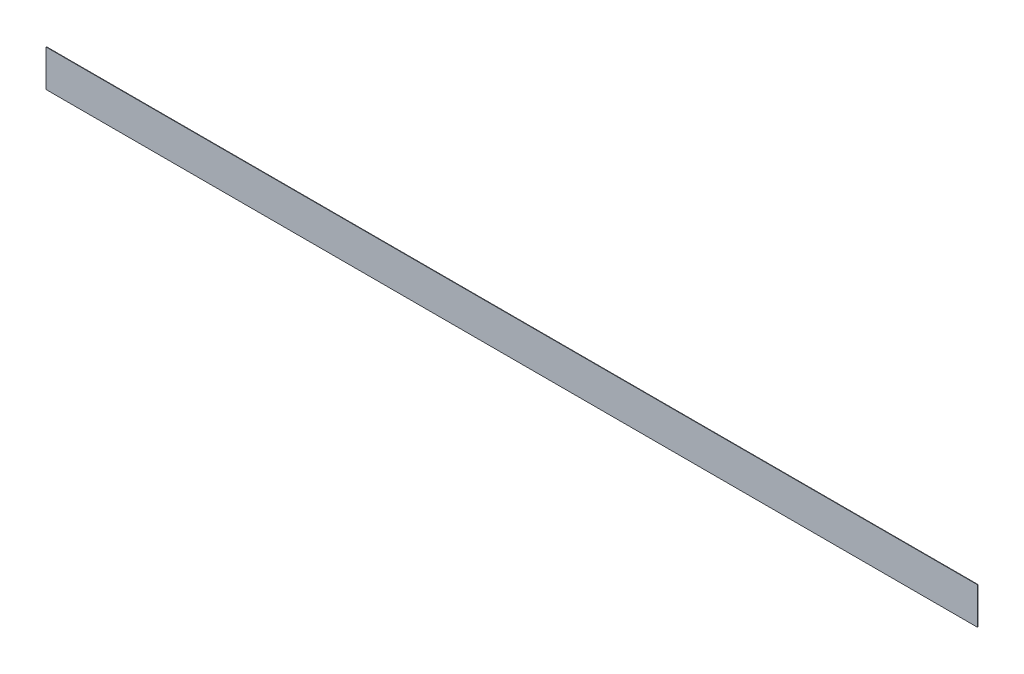
SolidWorks part; units mm, degrees
ref_plane "Front Plane" through (0, 0, 0) normal (0, 0, 1) x (1, 0, 0)
ref_plane "Top Plane" through (0, 0, 0) normal (0, 1, 0) x (1, 0, 0)
ref_plane "Right Plane" through (0, 0, 0) normal (1, 0, 0) x (0, 0, -1)
sketch "Sketch1" plane through (0, 0, 0) normal (0, 0, 1) x (1, 0, 0)
  line L0 (-12838.1061, 0) -> (-12838.1061, 482.6) construction
  line L1 (0, 0) -> (-12838.1061, 0)
  line L2 (0, 0) -> (0, 508)
  line L3 (0, 508) -> (-12838.1061, 508)
  line L4 (0, 0) -> (0, 482.6)
  line L5 (0, 482.6) -> (-336.55, 482.6)
  line L6 (-336.55, 482.6) -> (-336.55, 0)
  line L7 (-336.55, 0) -> (0, 0)
  line L8 (0, 0) -> (0, 482.6)
  line L9 (0, 482.6) -> (-336.55, 482.6)
  line L10 (-336.55, 482.6) -> (-336.55, 0)
  line L11 (-336.55, 0) -> (0, 0)
  line L12 (-12838.1061, 0) -> (-12838.1061, 508)
  line L14 (-12493.625, 508) -> (-11350.625, 508) construction
  dimension "D1" = 0
extrude "Boss-Extrude1" add sketch "Sketch1" against normal up to surface (6.35 mm away) contours L9 L10 L1 L2 | L12 L1 L10 L9 L2 L3
